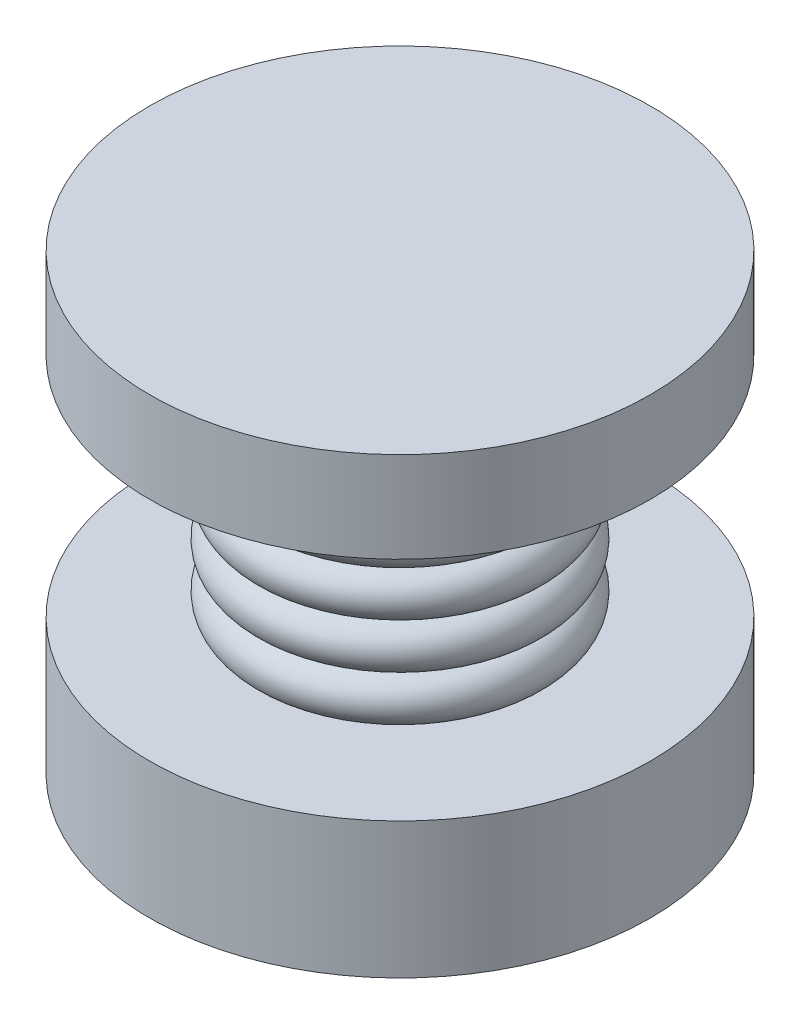
SolidWorks part; units mm, degrees
material "Резина"
ref_plane "Спереди" through (0, 0, 0) normal (0, 0, 1) x (1, 0, 0)
ref_plane "Сверху" through (0, 0, 0) normal (0, 1, 0) x (1, 0, 0)
ref_plane "Справа" through (0, 0, 0) normal (1, 0, 0) x (0, 0, -1)
sketch "Эскиз1" plane through (0, 0, 0) normal (0, 0, 1) x (1, 0, 0)
  line L0 (0, 0) -> (-2.7609, 0)
  line L1 (-2.7609, 0) -> (-2.7609, 1.5)
  line L2 (-2.7609, 1.5) -> (-1.3804, 1.5)
  line L3 (-1.3804, 1.5) -> (-1.3804, 4)
  line L4 (-1.3804, 4) -> (-2.7609, 4)
  line L5 (-2.7609, 4) -> (-2.7609, 5)
  line L6 (-2.7609, 5) -> (0, 5)
  line L7 (0, 5) -> (0, 0)
  circle A0 centre (-1.3804, 3.75) radius 0.25
  circle A1 centre (-1.3804, 3.25) radius 0.25
  circle A2 centre (-1.3804, 2.75) radius 0.25
  circle A3 centre (-1.3804, 2.25) radius 0.25
  circle A4 centre (-1.3804, 1.75) radius 0.25
  dimension "D1" = 0.5
  dimension "D2" = 5
  dimension "D3" = 1
  dimension "D4" = 1.5
  dimension "D5" = 5
revolve "Повернуть1" add sketch "Эскиз1" angle 360 about L7
